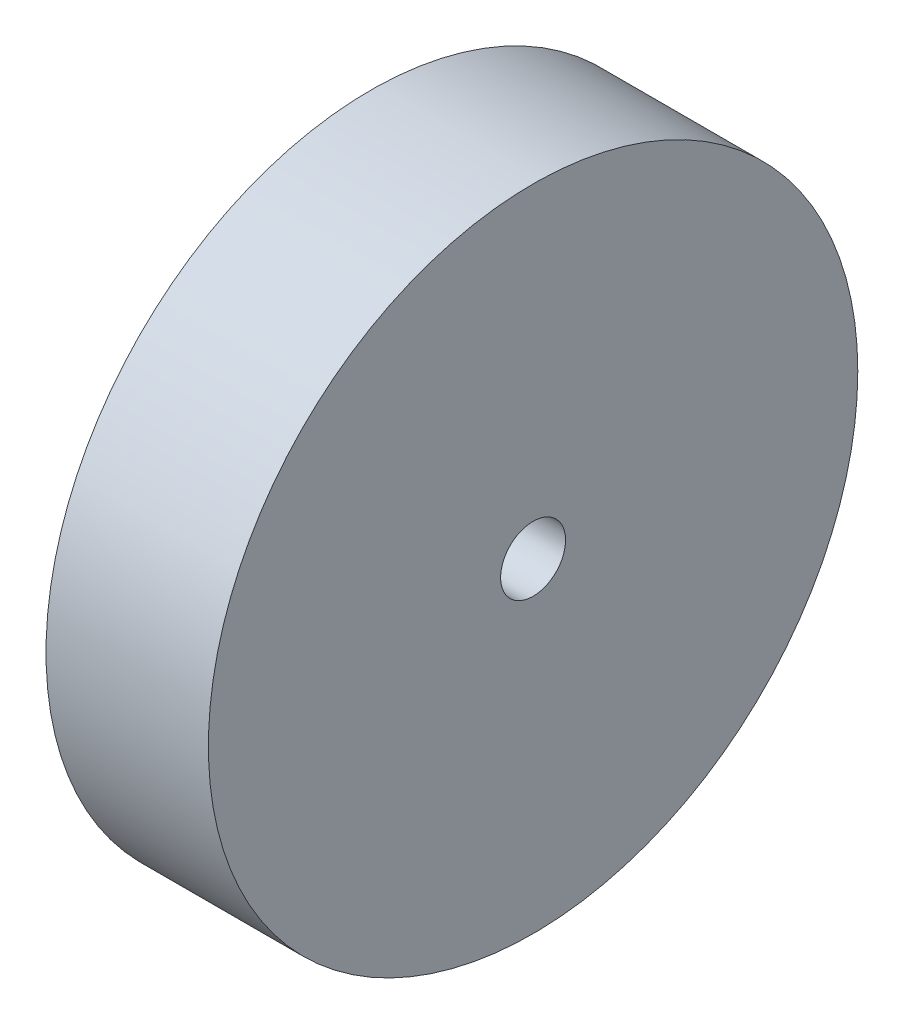
SolidWorks part; units mm, degrees
ref_plane "前视基准面" through (0, 0, 0) normal (0, 0, 1) x (1, 0, 0)
ref_plane "上视基准面" through (0, 0, 0) normal (0, 1, 0) x (1, 0, 0)
ref_plane "右视基准面" through (0, 0, 0) normal (1, 0, 0) x (0, 0, -1)
sketch "草图1" plane through (0, 0, 0) normal (1, 0, 0) x (0, 0, -1)
  circle A0 centre (0, 0) radius 10
  circle A1 centre (0, 0) radius 1
extrude "凸台-拉伸1" add sketch "草图1" along normal blind 5
